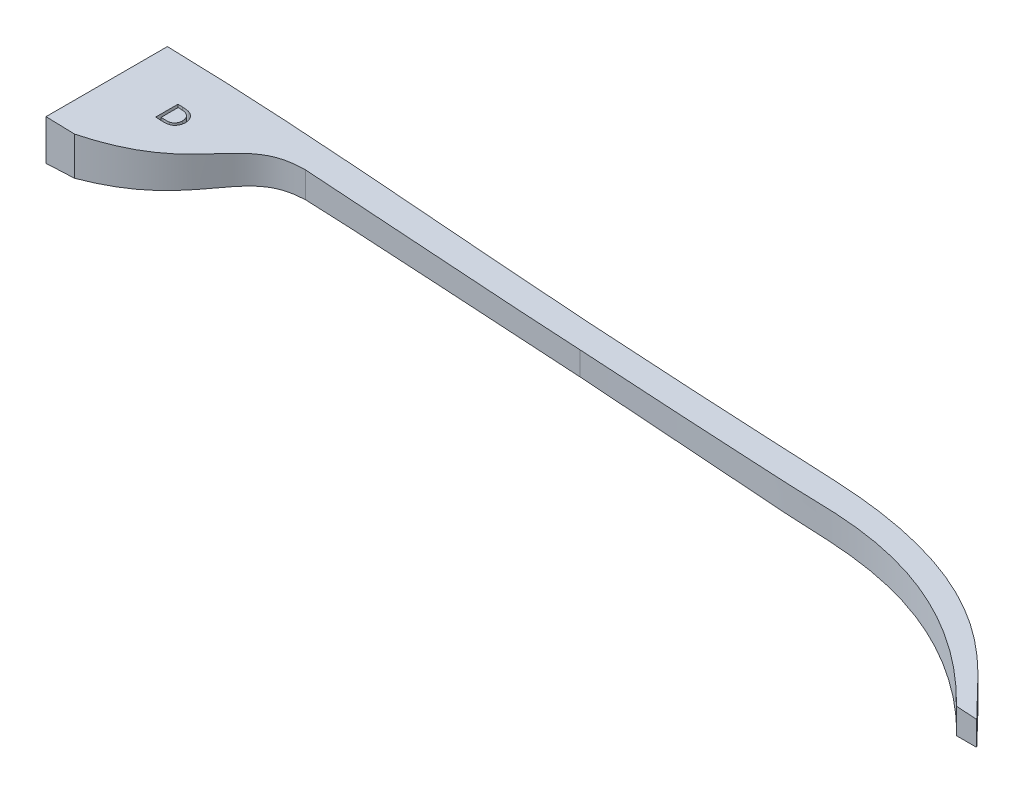
SolidWorks part; units mm, degrees
ref_plane "Front Plane" through (0, 0, 0) normal (0, 0, 1) x (1, 0, 0)
ref_plane "Top Plane" through (0, 0, 0) normal (0, 1, 0) x (1, 0, 0)
ref_plane "Right Plane" through (0, 0, 0) normal (1, 0, 0) x (0, 0, -1)
sketch "Sketch1" plane through (0, 0, 0) normal (0, 1, 0) x (1, 0, 0)
  line L1 (0, 0) -> (146.05, 0)
  line L2 (0, 0) -> (0, 19.05)
  line L3 (0, 19.05) -> (146.05, 19.05)
  line L4 (146.05, 0) -> (146.05, 19.05)
  dimension "D1" = 146.05
  dimension "D2" = 19.05
extrude "Boss-Extrude1" add sketch "Sketch1" along normal blind 12.7
sketch "Sketch3" plane through (0, 0, -19.05) normal (0, 0, -1) x (-1, 0, 0)
  line L0 (0, 12.7) -> (0, 0) construction
  line L1 (-146.05, 12.7) -> (-146.05, 0) construction
  spline S0 degree 3 poles (0, 6.35) (-24.1133, 7.4339) (-15.6413, 8.1962) (-82.0644, 3.4488) (-144.4619, -1.2779) (-146.05, 0) knots 0 0 0 0 0.484783 0.563884 1 1 1 1
  spline S1 degree 3 poles (0, 12.7) (-20.0076, 12.2633) (-68.5416, 7.1626) (-117.3282, 5.6847) (-146.05, 3.81) knots 0 0 0 0 0.409814 1 1 1 1
  point P6 (0, 0)
  point P11 (0, 0)
  point P13 (-71.5034, 4.9611)
  point P14 (-53.5606, 5.4839)
  line M1 (-146.05, 0) -> (0, 0)
  line M2 (0, 0) -> (0, 12.7)
  line M3 (0, 12.7) -> (-146.05, 12.7)
  line M4 (-146.05, 12.7) -> (-146.05, 0)
  dimension "D1" = 6.35
  dimension "D2" = 3.81
  dimension "D3" = 4.445
  dimension "D4" = 3.6908
  dimension "D5" = 3.6908
sketch "Sketch6" plane through (0, 12.7, 0) normal (0, 1, 0) x (1, 0, 0)
  text T0 "<b>D</b>"
  point P1 (7.9378, 8.8217)
extrude "Cut-Extrude5" cut sketch "Sketch6" against normal blind 1.905
sketch "Sketch4" plane through (0, 12.7, 0) normal (0, 1, 0) x (1, 0, 0)
  line L0 (146.05, 19.05) -> (0, 19.05) construction
  line L3 (4.4767, 0) -> (142.875, 0)
  line L4 (146.05, 0) -> (146.05, 19.05)
  line L5 (146.05, 19.05) -> (104.3032, 19.05)
  line L6 (0, 0) -> (146.05, 0) construction
  line L7 (146.05, 0) -> (146.05, 19.05) construction
  spline S0 degree 3 poles (4.4767, 0) (17.7258, 4.0431) (17.0053, 14.2049) (37.6932, 14.9861) (95.0665, 14.824) (108.0685, 14.714) (127.2268, 16.0497) (142.875, 0) knots 0 0 0 0 0.256127 0.322877 0.629203 0.700745 1 1 1 1
  spline S1 degree 3 poles (104.3032, 19.05) (131.3235, 19.1838) (139.2243, 6.6595) (146.05, 0) knots 0 0 0 0 1 1 1 1
  spline S2 degree 1 poles (26.2195, 14.4658) (68.9239, 14.8611) knots 0 0 1 1
  line M2 (146.05, 19.05) -> (0, 19.05)
  line M4 (0, 0) -> (146.05, 0)
  dimension "D1" = 3.175
extrude "Cut-Extrude2" cut sketch "Sketch4" against normal blind 19.05 contours S2 S0 M4 | S1 L4 M2
extrude "Cut-Extrude3" cut sketch "Sketch3" against normal through all contours S0 M2 M1 | S1 M3 M4
sketch "Sketch5" plane through (0, 0, 0) normal (-1, 0, 0) x (0, 0, 1)
  line L0 (0, 6.35) -> (-19.05, 6.35) construction
  line L1 (-5.715, 6.35) -> (-12.7, 6.35)
  line L2 (-5.715, 6.35) -> (-5.715, 10.16)
  line L3 (-5.715, 10.16) -> (-12.7, 10.16)
  line L4 (-12.7, 6.35) -> (-12.7, 10.16)
  line L5 (-19.05, 12.7) -> (-19.05, 6.35) construction
  dimension "D1" = 3.81
  dimension "D2" = 6.985
  dimension "D3" = 6.35
extrude "Cut-Extrude4" cut sketch "Sketch5" against normal blind 6.35
